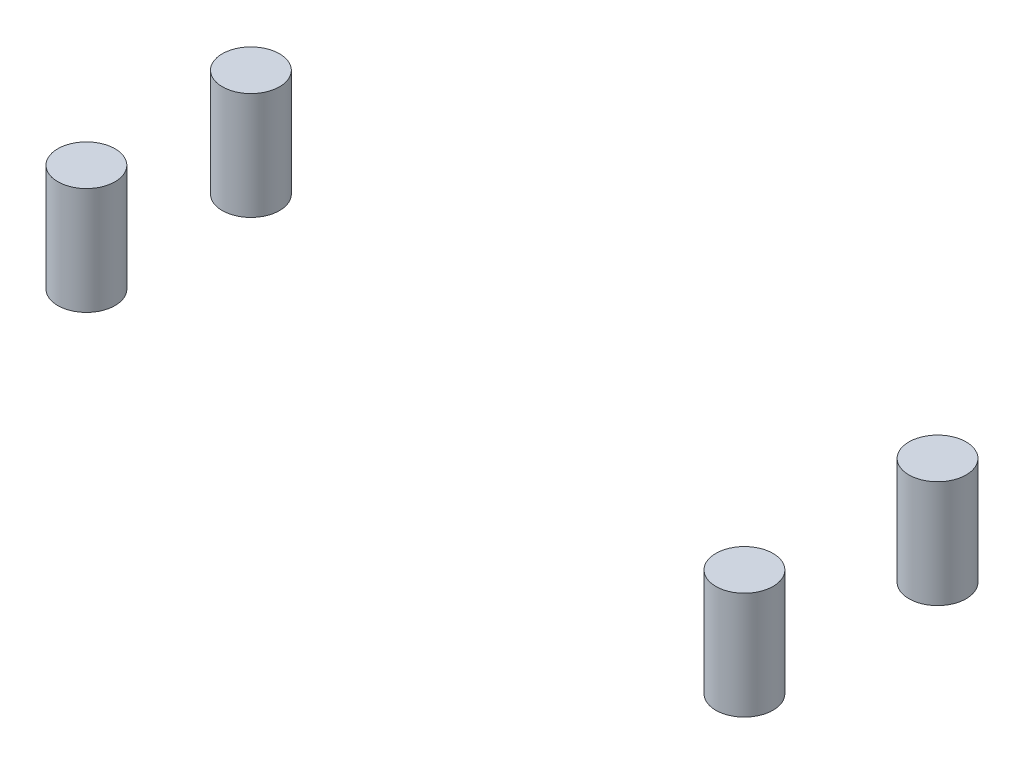
SolidWorks part; units mm, degrees
ref_plane "Front Plane" through (0, 0, 0) normal (0, 0, 1) x (1, 0, 0)
ref_plane "Top Plane" through (0, 0, 0) normal (0, 1, 0) x (1, 0, 0)
ref_plane "Right Plane" through (0, 0, 0) normal (1, 0, 0) x (0, 0, -1)
sketch "Sketch1" plane through (0, 0, 0) normal (0, 1, 0) x (1, 0, 0)
  line L0 (-72.9192, -33.04) -> (82.4403, -33.04) construction
  line L1 (-43.7, 11.96) -> (51.3, -14.04) construction
  line L2 (51.3, 12.96) -> (-43.7, -11.04) construction
  line L3 (-43.7, 11.96) -> (-43.7, -11.04) construction
  line L4 (-43.7, -11.04) -> (51.3, -14.04) construction
  circle A0 centre (-43.7, 11.96) radius 4
  circle A1 centre (-43.7, -11.04) radius 4
  circle A2 centre (51.3, -14.04) radius 4
  circle A3 centre (51.3, 12.96) radius 4
  point P10 (0, 0)
  dimension "D1" = 22
  dimension "D6" = 8
  dimension "D2" = 45
  dimension "D3" = 19
  dimension "D4" = 46
  dimension "D5" = 95
extrude "Boss-Extrude1" add sketch "Sketch1" along normal blind 15
ref_point "Point1"
ref_point "Point2"
ref_point "Point3"
